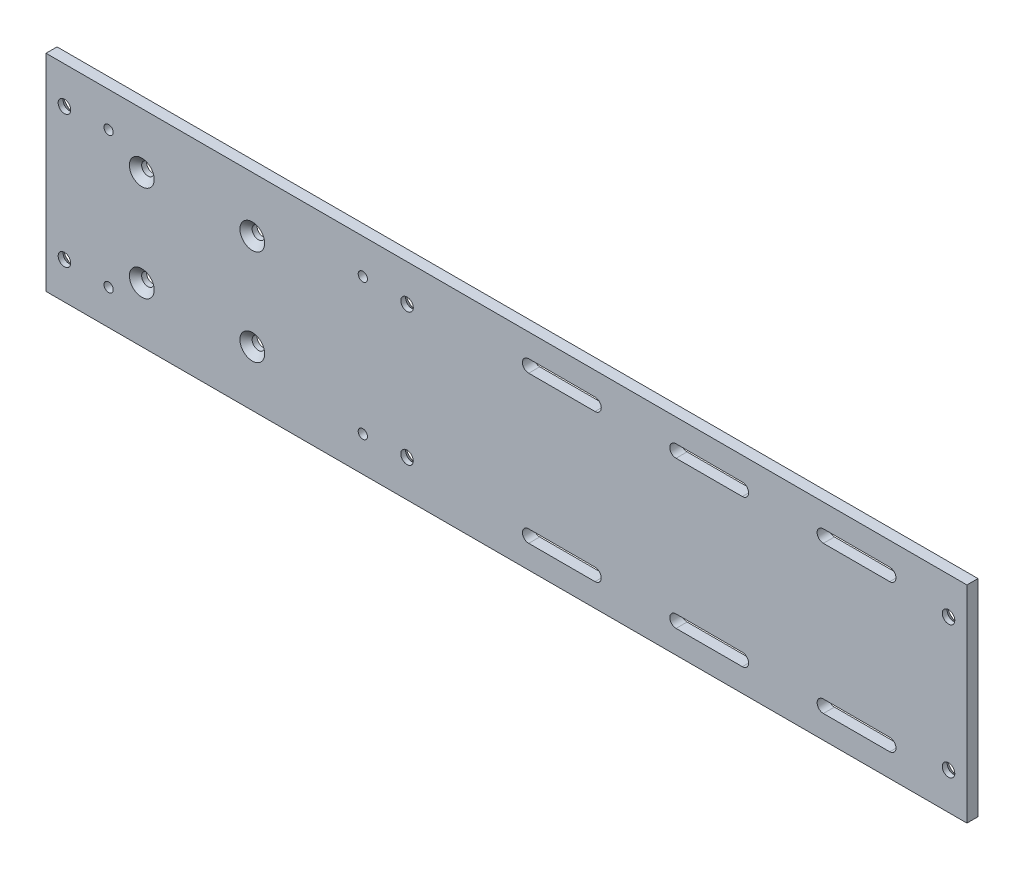
SolidWorks part; units mm, degrees
material "Сплав 2024"
ref_plane "Спереди" through (0, 0, 0) normal (0, 0, 1) x (1, 0, 0)
ref_plane "Сверху" through (0, 0, 0) normal (0, 1, 0) x (1, 0, 0)
ref_plane "Справа" through (0, 0, 0) normal (1, 0, 0) x (0, 0, -1)
sketch "Эскиз1" plane through (0, 0, 0) normal (0, 0, 1) x (1, 0, 0)
  line L1 (-125, 28) -> (125, 28)
  line L2 (-125, 28) -> (-125, -28)
  line L3 (-125, -28) -> (125, -28)
  line L4 (125, 28) -> (125, -28)
  line L5 (-125, 28) -> (125, -28) construction
  line L6 (-125, -28) -> (125, 28) construction
  point P0 (0, 0)
  dimension "D1" = 250
  dimension "D2" = 56
extrude "Бобышка-Вытянуть1" add sketch "Эскиз1" along normal blind 3
sketch "Эскиз2" plane through (0, 0, 3) normal (0, 0, 1) x (1, 0, 0)
  line L0 (-125, 0) -> (125, 0) construction
  line L1 (-125, 28) -> (-125, -28) construction
  line L2 (125, -28) -> (125, 28) construction
  line L3 (-20, 11) -> (-30, 11) construction
  line L4 (-25, 11) -> (22, 11) construction
  line L5 (-25, 11) -> (-25, -11) construction
  line L6 (-25, -11) -> (22, -11) construction
  line L7 (22, 11) -> (22, -11) construction
  line L8 (-25, 11) -> (22, -11) construction
  line L9 (-25, -11) -> (22, 11) construction
  line L10 (-20, 9.3) -> (-30, 9.3)
  line L11 (-20, 12.7) -> (-30, 12.7)
  line L12 (27, 11) -> (17, 11) construction
  line L13 (27, 9.3) -> (17, 9.3)
  line L14 (27, 12.7) -> (17, 12.7)
  line L15 (-20, -11) -> (-30, -11) construction
  line L16 (-20, -12.7) -> (-30, -12.7)
  line L17 (-20, -9.3) -> (-30, -9.3)
  line L18 (27, -11) -> (17, -11) construction
  line L19 (27, -12.7) -> (17, -12.7)
  line L20 (27, -9.3) -> (17, -9.3)
  arc A0 (-20, 9.3) -> (-20, 12.7) centre (-20, 11) ccw
  arc A1 (-30, 12.7) -> (-30, 9.3) centre (-30, 11) ccw
  arc A2 (27, 9.3) -> (27, 12.7) centre (27, 11) ccw
  arc A3 (17, 12.7) -> (17, 9.3) centre (17, 11) ccw
  arc A4 (-20, -12.7) -> (-20, -9.3) centre (-20, -11) ccw
  arc A5 (-30, -9.3) -> (-30, -12.7) centre (-30, -11) ccw
  arc A6 (27, -12.7) -> (27, -9.3) centre (27, -11) ccw
  arc A7 (17, -9.3) -> (17, -12.7) centre (17, -11) ccw
  point P6 (-1.5, 0)
  point P13 (-25, 11)
  point P21 (22, 11)
  point P28 (-25, -11)
  point P35 (22, -11)
  dimension "D4" = 1.7
  dimension "D1" = 22
  dimension "D2" = 47
  dimension "D3" = 100
  dimension "D5" = 10
  dimension "D6" = 2
  dimension "D7" = 2
extrude "Вырез-Вытянуть1" [suppressed] cut sketch "Эскиз2" against normal through all
sketch "Эскиз3" plane through (0, 0, 3) normal (0, 0, 1) x (1, 0, 0)
  line L0 (125, 0) -> (-80.1338, 0) construction
  line L1 (125, -28) -> (125, 28) construction
  line L2 (125, 18) -> (-68.9479, 18) construction
  line L3 (-99, 13) -> (-69, 13) construction
  line L4 (-99, 13) -> (-99, -13) construction
  line L5 (-99, -13) -> (-69, -13) construction
  line L6 (-69, 13) -> (-69, -13) construction
  line L7 (-99, 13) -> (-69, -13) construction
  line L8 (-99, -13) -> (-69, 13) construction
  line L9 (125, -18) -> (-68.9479, -18) construction
  line L10 (-125, 28) -> (-125, -28) construction
  point P5 (-84, 0)
  dimension "D5" = 26
  dimension "D1" = 36
  dimension "D2" = 18
  dimension "D3" = 30
  dimension "D4" = 26
hole_wizard "Зенковка для  винта с потайной головкой с внутренним шестигранником M32" positions "Эскиз9" profile "Эскиз8" countersink size "M3" standard "Ansi Metric" end condition through all
sketch "Эскиз9" plane through (0, 0, 3) normal (0, 0, 1) x (1, 0, 0)
  point P0 (-99, 13)
  point P3 (-99, -13)
  point P6 (-69, -13)
  point P9 (-69, 13)
sketch "Эскиз8" plane through (-99, 13, 3) normal (1, 0, 0) x (0, -1, 0)
  line L0 (0, 0) -> (0, 3)
  line L1 (0, 3) -> (1.7, 3)
  line L2 (1.7, 3) -> (1.7, 1.66)
  line L3 (1.7, 1.66) -> (3.36, 0)
  line L5 (3.36, 0) -> (0, 0)
  line L6 (-1.7, 1.66) -> (-3.36, 0) construction
  line L11 (0, -6.35) -> (0, 107.95) construction
  dimension "Диаметр сквозного отверстия" = 3.4
  dimension "Глубина сквозного отверстия" = 3
  dimension "Диаметр передней зенковки" = 6.72
  dimension "Угол передней зенковки" = 90
sketch "Эскиз4" plane through (0, 0, 0) normal (0, 0, 1) x (1, 0, 0)
  line L0 (120, 28) -> (120, -28) construction
  line L1 (125, 28) -> (-125, 28) construction
  line L2 (-125, -28) -> (125, -28) construction
  line L3 (-120, 28) -> (-120, -28) construction
  line L4 (-125, 28) -> (-125, -28) construction
  line L5 (125, -28) -> (125, 28) construction
  line L6 (-125, 18) -> (125, 18) construction
  line L7 (-125, -18) -> (125, -18) construction
  line L8 (-27, -28) -> (-27, 28) construction
  line L9 (-125, -28) -> (125, -28) construction
  line L10 (125, 28) -> (-125, 28) construction
  line L11 (-125, 28) -> (-125, -28) construction
  dimension "D1" = 5
  dimension "D2" = 5
  dimension "D3" = 10
  dimension "D4" = 10
  dimension "D5" = 98
hole_wizard "Зенковка для  винта с потайной головкой с внутренним шестигранником M31" positions "Эскиз6" profile "Эскиз5" countersink size "M3" standard "Ansi Metric" end condition through all
sketch "Эскиз6" plane through (83.0894, 2.1664, 0) normal (0, 0, 1) x (1, 0, 0)
  line L0 (-203.0894, 25.8336) -> (-203.0894, -30.1664) construction
  line L1 (-208.0894, 15.8336) -> (41.9106, 15.8336) construction
  line L2 (-208.0894, -20.1664) -> (41.9106, -20.1664) construction
  line L3 (36.9106, 25.8336) -> (36.9106, -30.1664) construction
  line L4 (-110.0894, -30.1664) -> (-110.0894, 25.8336) construction
  point P0 (-203.0894, 15.8336)
  point P6 (-203.0894, -20.1664)
  point P10 (36.9106, 15.8336)
  point P14 (36.9106, -20.1664)
  point P17 (-110.0894, 15.8336)
  point P21 (-110.0894, -20.1664)
sketch "Эскиз5" plane through (-120, 18, 0) normal (1, 0, 0) x (0, 1, 0)
  line L0 (0, 0) -> (0, 3)
  line L1 (0, 3) -> (1.7, 3)
  line L2 (1.7, 3) -> (1.7, 1.66)
  line L3 (1.7, 1.66) -> (3.36, 0)
  line L5 (3.36, 0) -> (0, 0)
  line L6 (-1.7, 1.66) -> (-3.36, 0) construction
  line L11 (0, -6.35) -> (0, 107.95) construction
  dimension "Диаметр сквозного отверстия" = 3.4
  dimension "Глубина сквозного отверстия" = 3
  dimension "Диаметр передней зенковки" = 6.72
  dimension "Угол передней зенковки" = 90
sketch "Эскиз7" plane through (0, 0, 3) normal (0, 0, 1) x (1, 0, 0)
  line L0 (125, 0) -> (-125, 0) construction
  line L1 (125, -28) -> (125, 28) construction
  line L2 (-125, 28) -> (-125, -28) construction
  line L3 (6.0305, 20) -> (24.0305, 20) construction
  line L4 (15.0305, 20) -> (55.0305, 20) construction
  line L5 (15.0305, 20) -> (15.0305, -20) construction
  line L6 (15.0305, -20) -> (55.0305, -20) construction
  line L7 (55.0305, 20) -> (55.0305, -20) construction
  line L8 (15.0305, 20) -> (55.0305, -20) construction
  line L9 (15.0305, -20) -> (55.0305, 20) construction
  line L10 (6.0305, 21.7) -> (24.0305, 21.7)
  line L11 (6.0305, 18.3) -> (24.0305, 18.3)
  line L12 (46.0305, 20) -> (64.0305, 20) construction
  line L13 (46.0305, 21.7) -> (64.0305, 21.7)
  line L14 (46.0305, 18.3) -> (64.0305, 18.3)
  line L15 (86.0305, 20) -> (104.0305, 20) construction
  line L16 (86.0305, 21.7) -> (104.0305, 21.7)
  line L17 (86.0305, 18.3) -> (104.0305, 18.3)
  line L18 (6.0305, -20) -> (24.0305, -20) construction
  line L19 (6.0305, -18.3) -> (24.0305, -18.3)
  line L20 (6.0305, -21.7) -> (24.0305, -21.7)
  line L21 (46.0305, -20) -> (64.0305, -20) construction
  line L22 (46.0305, -18.3) -> (64.0305, -18.3)
  line L23 (46.0305, -21.7) -> (64.0305, -21.7)
  line L24 (86.0305, -20) -> (104.0305, -20) construction
  line L25 (86.0305, -18.3) -> (104.0305, -18.3)
  line L26 (86.0305, -21.7) -> (104.0305, -21.7)
  arc A0 (6.0305, 21.7) -> (6.0305, 18.3) centre (6.0305, 20) ccw
  arc A1 (24.0305, 18.3) -> (24.0305, 21.7) centre (24.0305, 20) ccw
  arc A2 (46.0305, 21.7) -> (46.0305, 18.3) centre (46.0305, 20) ccw
  arc A3 (64.0305, 18.3) -> (64.0305, 21.7) centre (64.0305, 20) ccw
  arc A4 (86.0305, 21.7) -> (86.0305, 18.3) centre (86.0305, 20) ccw
  arc A5 (104.0305, 18.3) -> (104.0305, 21.7) centre (104.0305, 20) ccw
  arc A6 (6.0305, -18.3) -> (6.0305, -21.7) centre (6.0305, -20) ccw
  arc A7 (24.0305, -21.7) -> (24.0305, -18.3) centre (24.0305, -20) ccw
  arc A8 (46.0305, -18.3) -> (46.0305, -21.7) centre (46.0305, -20) ccw
  arc A9 (64.0305, -21.7) -> (64.0305, -18.3) centre (64.0305, -20) ccw
  arc A10 (86.0305, -18.3) -> (86.0305, -21.7) centre (86.0305, -20) ccw
  arc A11 (104.0305, -21.7) -> (104.0305, -18.3) centre (104.0305, -20) ccw
  point P6 (35.0305, 0)
  point P13 (15.0305, 20)
  point P21 (55.0305, 20)
  point P28 (95.0305, 20)
  point P35 (15.0305, -20)
  point P42 (55.0305, -20)
  point P49 (95.0305, -20)
  dimension "D4" = 1.7
  dimension "D1" = 40
  dimension "D2" = 40
  dimension "D3" = 3
  dimension "D5" = 18
  dimension "D6" = 2
extrude "Вырез-Вытянуть3" cut sketch "Эскиз7" against normal through all
sketch "Эскиз11" plane through (0, 0, 3) normal (0, 0, 1) x (1, 0, 0)
  line L0 (-125, 0) -> (-92.9583, 0) construction
  line L1 (-125, 28) -> (-125, -28) construction
  line L3 (-108, 18.5) -> (-39, 18.5) construction
  line L4 (-108, 18.5) -> (-108, -18.5) construction
  line L5 (-108, -18.5) -> (-39, -18.5) construction
  line L6 (-39, 18.5) -> (-39, -18.5) construction
  line L7 (-108, 18.5) -> (-39, -18.5) construction
  line L8 (-108, -18.5) -> (-39, 18.5) construction
  point P5 (-73.5, 0)
  dimension "D1" = 69
  dimension "D2" = 37
  dimension "D3" = 17
hole_wizard "Отверстие обработанное метчиком M3x0.51" positions "Эскиз13" profile "Эскиз12" tap size "M3x0.5" standard "Ansi Metric" end condition through all
sketch "Эскиз13" plane through (0, 0, 3) normal (0, 0, 1) x (1, 0, 0)
  point P0 (-108, 18.5)
  point P3 (-108, -18.5)
  point P6 (-39, -18.5)
  point P9 (-39, 18.5)
sketch "Эскиз12" plane through (-108, 18.5, 3) normal (1, 0, 0) x (0, -1, 0)
  line L0 (0, 0) -> (0, 3)
  line L1 (0, 3) -> (1.25, 3)
  line L2 (1.25, 3) -> (1.25, 0)
  line L5 (1.25, 0) -> (0, 0)
  line L11 (0, -6.35) -> (0, 107.95) construction
  dimension "Диаметр проходного сверла" = 2.5
  dimension "Глубина проходного сверла" = 3
cosmetic thread "Отверстие резьбы1" parameters "D2"=3
cosmetic thread "Отверстие резьбы2" parameters "D2"=3
cosmetic thread "Отверстие резьбы3" parameters "D2"=3
cosmetic thread "Отверстие резьбы4" parameters "D2"=3
